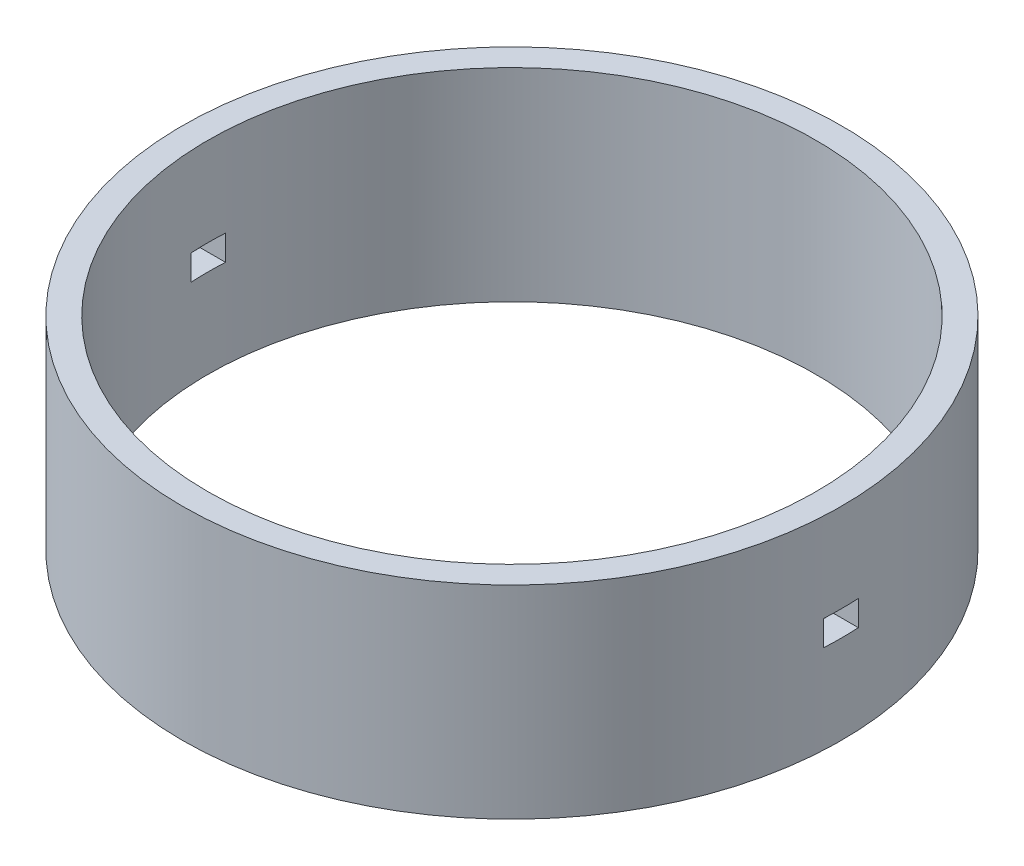
SolidWorks part; units mm, degrees
ref_plane "Front Plane" through (0, 0, 0) normal (0, 0, 1) x (1, 0, 0)
ref_plane "Top Plane" through (0, 0, 0) normal (0, 1, 0) x (1, 0, 0)
ref_plane "Right Plane" through (0, 0, 0) normal (1, 0, 0) x (0, 0, -1)
sketch "Sketch1" plane through (0, 0, 0) normal (0, 1, 0) x (1, 0, 0)
  circle A0 centre (0, 0) radius 1981.2
  circle A1 centre (0, 0) radius 1828.8
  dimension "D1" = 3962.4
  dimension "D2" = 3657.6
extrude "Boss-Extrude1" add sketch "Sketch1" along normal mid plane 1219.2
sketch "Sketch2" plane through (0, 0, 0) normal (1, 0, 0) x (0, 0, -1)
  line L1 (-104.14, -76.2) -> (104.14, -76.2)
  line L2 (-104.14, -76.2) -> (-104.14, 76.2)
  line L3 (-104.14, 76.2) -> (104.14, 76.2)
  line L4 (104.14, -76.2) -> (104.14, 76.2)
  line L5 (-104.14, -76.2) -> (104.14, 76.2) construction
  line L6 (-104.14, 76.2) -> (104.14, -76.2) construction
  point P0 (0, 0)
  dimension "D1" = 152.4
  dimension "D2" = 208.28
extrude "Cut-Extrude1" cut sketch "Sketch2" against normal through all both and the other way through all
